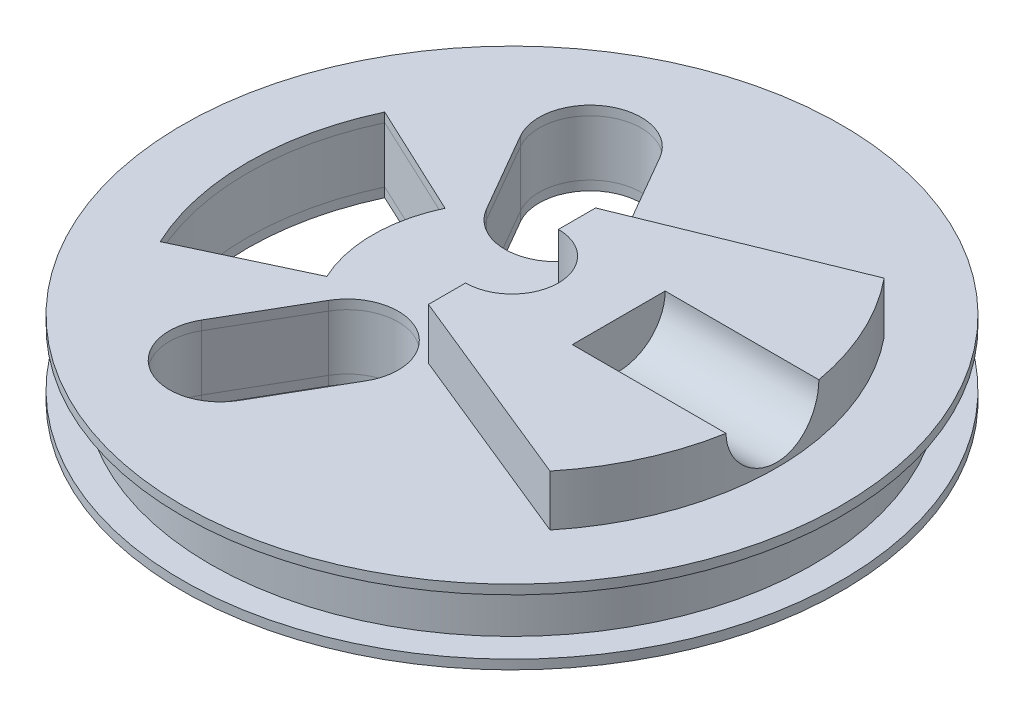
SolidWorks part; units mm, degrees
material "ABS"
ref_plane "前视基准面" through (0, 0, 0) normal (0, 0, 1) x (1, 0, 0)
ref_plane "上视基准面" through (0, 0, 0) normal (0, 1, 0) x (1, 0, 0)
ref_plane "右视基准面" through (0, 0, 0) normal (1, 0, 0) x (0, 0, -1)
sketch "Sketch1" plane through (0, 0, 0) normal (0, 1, 0) x (1, 0, 0)
  circle A0 centre (0, 0) radius 32.5
  circle A1 centre (0, 0) radius 5
  dimension "D1" = 65
  dimension "D2" = 10
extrude "Boss-Extrude1" add sketch "Sketch1" along normal blind 6
sketch "Sketch5" plane through (0, 6, 0) normal (0, 1, 0) x (1, 0, 0)
  line L0 (0, 9) -> (22.0964, 18)
  line L1 (0, -9) -> (22.0964, -18)
  line L2 (0, 0) -> (52.6815, 0) construction
  line L3 (0, -9) -> (0, -5)
  line L4 (0, 5) -> (0, 9)
  arc A1 (22.0964, -18) -> (22.0964, 18) centre (0, 0) ccw
  circle A2 centre (0, 0) radius 32.5 construction
  arc A4 (22.0964, 18) -> (22.0964, -18) centre (0, 0) ccw construction
  arc A5 (0, 9) -> (0, -9) centre (0, 0) ccw construction
  arc A6 (0, -5) -> (0, 5) centre (0, 0) ccw
  point P8 (0, 0)
  dimension "D1" = 4
  dimension "D3" = 18
extrude "Boss-Extrude3" add sketch "Sketch5" along normal blind 6.5
ref_plane "Plane1" through (28.5, 0, 0) normal (1, 0, 0) x (0, 0, -1)
sketch "Sketch6" plane through (28.5, 0, 0) normal (1, 0, 0) x (0, 0, -1)
  line L0 (18, 12.5) -> (-18, 12.5) construction
  circle A0 centre (0, 12.5) radius 5
  dimension "D1" = 10
extrude "Cut-Extrude1" cut sketch "Sketch6" against normal blind 17
sketch "Sketch11" plane through (0, 6, 0) normal (0, 1, 0) x (1, 0, 0)
  circle A2 centre (0, 0) radius 35.5
  circle A3 centre (0, 0) radius 35.5
  dimension "D1" = 3
extrude "Boss-Extrude4" add sketch "Sketch11" along normal blind 1 separate body
sketch "Sketch12" plane through (0, 0, 0) normal (0, -1, 0) x (1, 0, 0)
  circle A0 centre (0, 0) radius 35.5 construction
  circle A1 centre (0, 0) radius 35.5
extrude "Boss-Extrude5" add sketch "Sketch12" along normal blind 1 separate body
sketch "Sketch8" plane through (0, 6, 0) normal (0, 1, 0) x (1, 0, 0)
  line L0 (0, 0) -> (-37.0055, 0) construction
  line L1 (-11.5, 19.9186) -> (-6.5, 11.2583) construction
  line L2 (-6.7369, 22.6686) -> (-1.7369, 14.0083)
  line L3 (-16.2631, 17.1686) -> (-11.2631, 8.5083)
  line L4 (-11.5, -19.9186) -> (-6.5, -11.2583) construction
  line L5 (-6.7369, -22.6686) -> (-1.7369, -14.0083)
  line L6 (-16.2631, -17.1686) -> (-11.2631, -8.5083)
  arc A2 (-6.7369, 22.6686) -> (-16.2631, 17.1686) centre (-11.5, 19.9186) ccw
  arc A3 (-11.2631, 8.5083) -> (-1.7369, 14.0083) centre (-6.5, 11.2583) ccw
  arc A4 (-6.7369, -22.6686) -> (-16.2631, -17.1686) centre (-11.5, -19.9186) cw
  arc A5 (-11.2631, -8.5083) -> (-1.7369, -14.0083) centre (-6.5, -11.2583) cw
  point P5 (-9, 15.5885)
  point P13 (-9, -15.5885)
  dimension "D1" = 60
  dimension "D3" = 5.5
  dimension "D2" = 10
  dimension "D4" = 13
sketch "Sketch10" plane through (0, 6, 0) normal (0, 1, 0) x (1, 0, 0)
  line L0 (-13.5821, 6.3661) -> (-25.8044, 12.0949)
  line L1 (0, 0) -> (-37.0055, 0) construction
  line L2 (0, 0) -> (-37.0055, 0) construction
  line L3 (-13.5821, -6.3661) -> (-25.8044, -12.0949)
  arc A0 (-13.5821, 6.3661) -> (-13.5821, -6.3661) centre (0, 0) ccw
  arc A1 (-25.8044, 12.0949) -> (-25.8044, -12.0949) centre (0, 0) ccw
  arc A2 (-25.8044, -12.0949) -> (-25.8044, 12.0949) centre (0, 0) ccw construction
  arc A3 (-13.5821, -6.3661) -> (-13.5821, 6.3661) centre (0, 0) ccw construction
  point P10 (-13.5821, 6.3661)
  dimension "D1" = 56.9966
  dimension "D2" = 30
extrude "Cut-Extrude4" cut sketch "Sketch10" against normal through all both and the other way through all
extrude "Cut-Extrude5" cut sketch "Sketch8" against normal through all both and the other way through all
